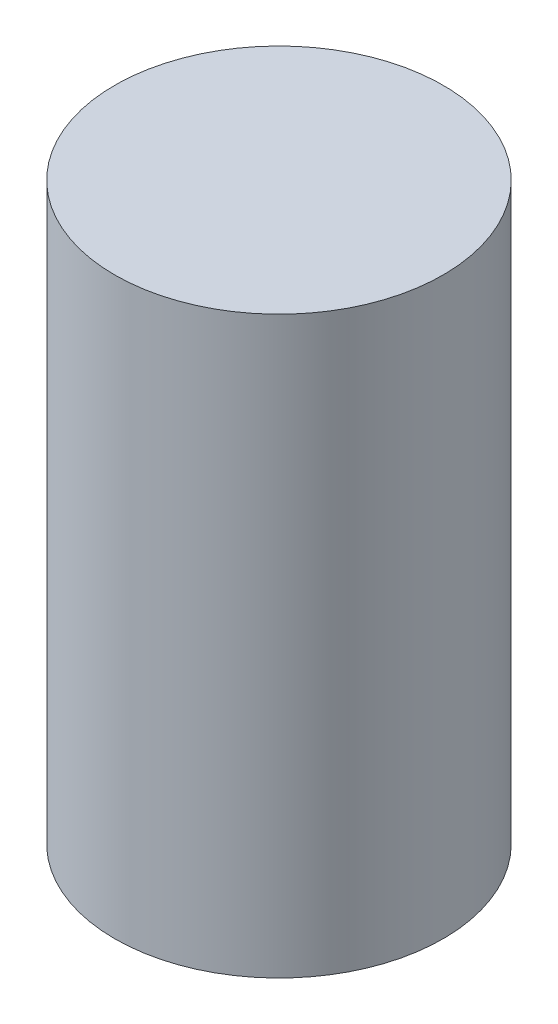
SolidWorks part; units mm, degrees
ref_plane "Front Plane" through (0, 0, 0) normal (0, 0, 1) x (1, 0, 0)
ref_plane "Top Plane" through (0, 0, 0) normal (0, 1, 0) x (1, 0, 0)
ref_plane "Right Plane" through (0, 0, 0) normal (1, 0, 0) x (0, 0, -1)
other "Configuration Table"
sketch "Sketch1" plane through (0, 0, 0) normal (0, 1, 0) x (1, 0, 0)
  circle A0 centre (0, 0) radius 4
extrude "VNT_nipel_M8" add sketch "Sketch1" along normal blind 14 from offset 30 separate body
